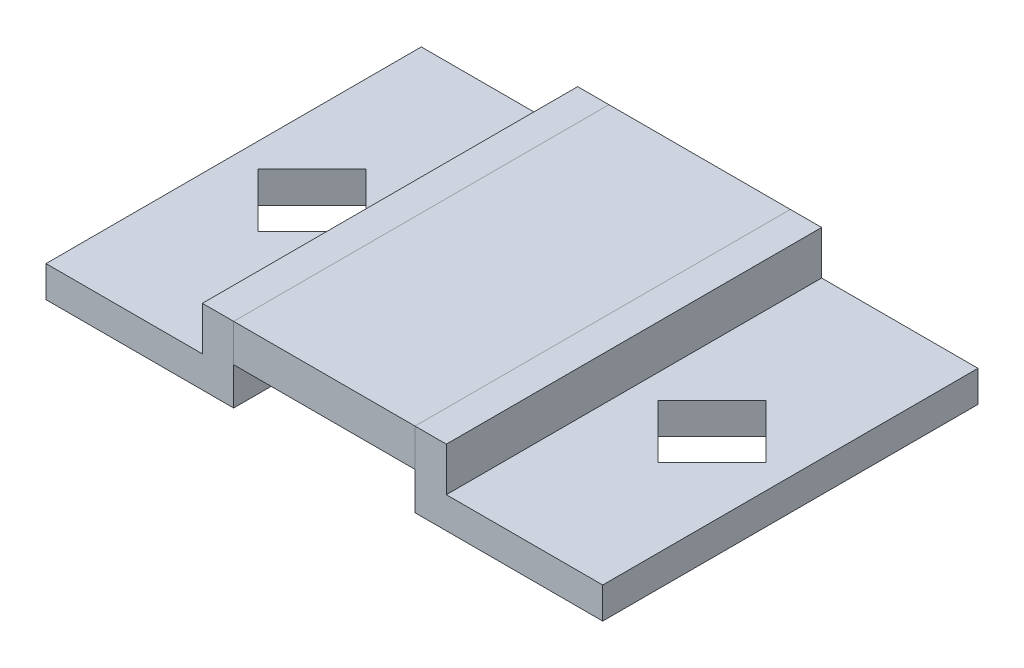
SolidWorks part; units mm, degrees
ref_plane "Front Plane" through (0, 0, 0) normal (0, 0, 1) x (1, 0, 0)
ref_plane "Top Plane" through (0, 0, 0) normal (0, 1, 0) x (1, 0, 0)
ref_plane "Right Plane" through (0, 0, 0) normal (1, 0, 0) x (0, 0, -1)
sketch "Sketch1" plane through (0, 0, 0) normal (0, 1, 0) x (1, 0, 0)
  line L1 (0, 0) -> (14.5, 0)
  line L2 (0, 0) -> (0, 30)
  line L3 (0, 30) -> (14.5, 30)
  line L4 (14.5, 0) -> (14.5, 30)
  dimension "D1" = 14.5
  dimension "D2" = 30
extrude "Boss-Extrude1" add sketch "Sketch1" along normal blind 3 contours L2 L3 L4 L1
sketch "Sketch2" plane through (0, 3, 0) normal (0, 1, 0) x (1, 0, 0)
  line L0 (14.5, 0) -> (14.5, 30) construction
  line L1 (0, 30) -> (-2.5, 30)
  line L2 (0, 30) -> (0, 0)
  line L3 (0, 0) -> (-2.5, 0)
  line L4 (-2.5, 30) -> (-2.5, 0)
  line L5 (14.5, 30) -> (17, 30)
  line L6 (14.5, 30) -> (14.5, 0)
  line L7 (14.5, 0) -> (17, 0)
  line L8 (17, 30) -> (17, 0)
  line L9 (0, 0) -> (14.5, 0) construction
  dimension "D1" = 2.5
extrude "Boss-Extrude2" add sketch "Sketch2" against normal blind 6 separate body
sketch "Sketch3" plane through (0, -3, 0) normal (0, -1, 0) x (1, 0, 0)
  line L0 (0, 0) -> (0, -30) construction
  line L1 (-2.5, -30) -> (-15, -30)
  line L2 (-2.5, -30) -> (-2.5, 0)
  line L3 (-2.5, 0) -> (-15, 0)
  line L4 (-15, -30) -> (-15, 0)
  line L5 (17, -30) -> (29.5, -30)
  line L6 (17, -30) -> (17, 0)
  line L7 (17, 0) -> (29.5, 0)
  line L8 (29.5, -30) -> (29.5, 0)
  line L9 (14.5, 0) -> (17, 0) construction
  line L10 (0, 0) -> (14.5, 0) construction
  dimension "D1" = 12.5
extrude "Boss-Extrude3" add sketch "Sketch3" against normal blind 2.5
sketch "Sketch4" plane through (0, -0.5, 0) normal (0, 1, 0) x (1, 0, 0)
  line L0 (-8.75, 30) -> (-8.75, 0) construction
  line L1 (-15, 30) -> (-2.5, 30) construction
  line L2 (-2.5, 0) -> (-15, 0) construction
  line L3 (23.25, 30) -> (23.25, 0) construction
  line L4 (17, 30) -> (29.5, 30) construction
  line L5 (29.5, 0) -> (17, 0) construction
  line L10 (-8.75, 19.3134) -> (-13.0634, 15)
  line L11 (-13.0634, 15) -> (-8.75, 10.6866)
  line L12 (-8.75, 10.6866) -> (-4.4366, 15)
  line L13 (-4.4366, 15) -> (-8.75, 19.3134)
  line L14 (7.25, 30) -> (7.25, 0) construction
  line L15 (0, 30) -> (14.5, 30) construction
  line L16 (0, 0) -> (14.5, 0) construction
  line L17 (23.25, 10.6866) -> (18.9366, 15)
  line L18 (27.5634, 15) -> (23.25, 10.6866)
  line L19 (23.25, 19.3134) -> (27.5634, 15)
  line L20 (18.9366, 15) -> (23.25, 19.3134)
  point P12 (-7.5, 10.4469)
  point P21 (-8.75, 15)
  dimension "D1" = 6.1
  dimension "D2" = 15
extrude "Cut-Extrude2" cut sketch "Sketch4" against normal through all
